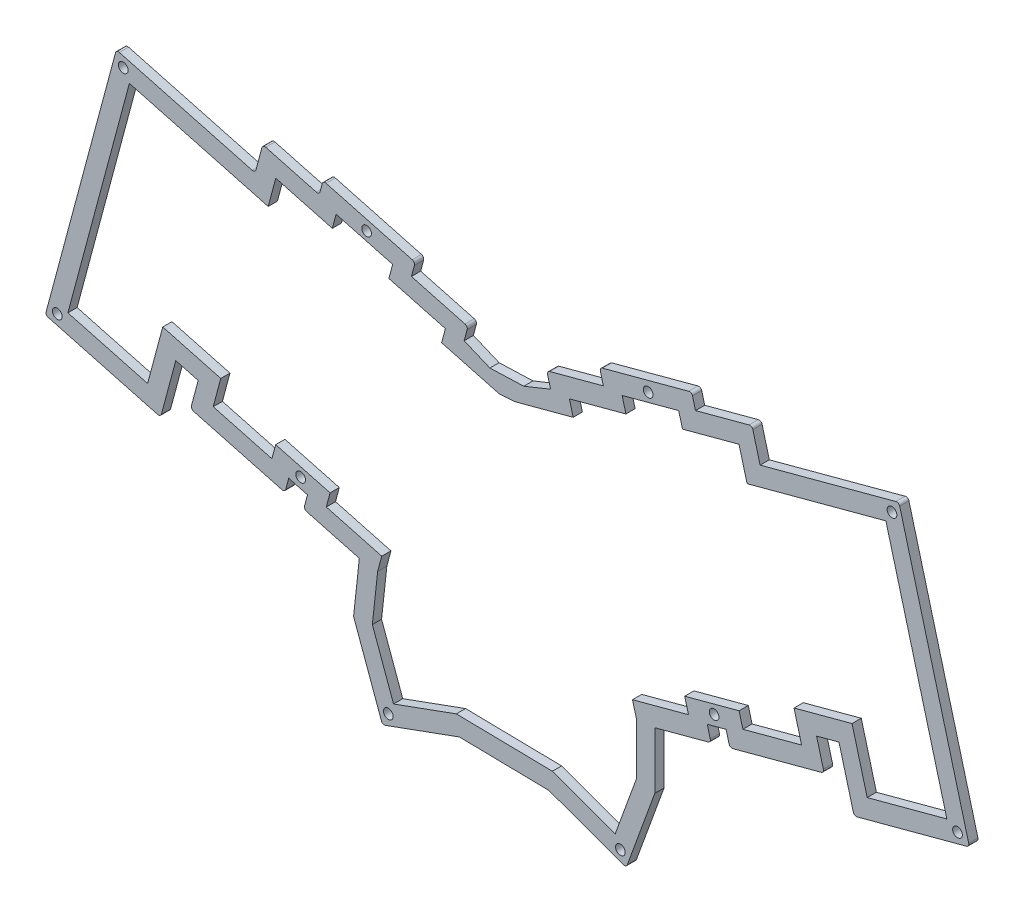
SolidWorks part; units mm, degrees
ref_plane "Front Plane" through (0, 0, 0) normal (0, 0, 1) x (1, 0, 0)
ref_plane "Top Plane" through (0, 0, 0) normal (0, 1, 0) x (1, 0, 0)
ref_plane "Right Plane" through (0, 0, 0) normal (1, 0, 0) x (0, 0, -1)
sketch "Model" plane through (0, 0, 0) normal (0, 0, 1) x (1, 0, 0)
  line L0 (282.165, 226.202) -> (288.4436, 227.8841) construction
  line L1 (267.373, 281.405) -> (273.6516, 283.0871) construction
  line L2 (195.392, 284.0785) -> (194.5766, 287.1211) construction
  line L3 (100.681, 283.685) -> (101.4961, 286.7277) construction
  line L4 (168.22, 168.742) -> (181.234, 164.006) construction
  line L5 (181.234, 164.006) -> (185.972, 177.021) construction
  line L6 (185.972, 177.021) -> (172.956, 181.758) construction
  line L7 (172.956, 181.758) -> (168.22, 168.742) construction
  line L8 (132.176, 184.752) -> (133.281, 181.717) construction
  line L9 (133.281, 181.717) -> (131.706, 181.144) construction
  line L10 (131.706, 181.144) -> (130.099, 185.56) construction
  line L11 (130.099, 185.56) -> (117.085, 180.823) construction
  line L12 (117.085, 180.823) -> (118.692, 176.407) construction
  line L13 (118.692, 176.407) -> (117.118, 175.834) construction
  line L14 (117.118, 175.834) -> (116.013, 178.869) construction
  line L15 (116.013, 178.869) -> (109.812, 176.612) construction
  line L16 (109.812, 176.612) -> (110.917, 173.576) construction
  line L17 (110.917, 173.576) -> (110.141, 173.294) construction
  line L18 (110.141, 173.294) -> (111.048, 170.804) construction
  line L19 (111.048, 170.804) -> (111.822, 171.086) construction
  line L20 (111.822, 171.086) -> (113.968, 165.194) construction
  line L21 (113.968, 165.194) -> (115.588, 165.784) construction
  line L22 (115.588, 165.784) -> (115.999, 164.656) construction
  line L23 (115.999, 164.656) -> (118.959, 165.734) construction
  line L24 (118.959, 165.734) -> (118.549, 166.861) construction
  line L25 (118.549, 166.861) -> (120.169, 167.452) construction
  line L26 (120.169, 167.452) -> (118.641, 171.651) construction
  line L27 (118.641, 171.651) -> (120.215, 172.224) construction
  line L28 (120.215, 172.224) -> (121.821, 167.809) construction
  line L29 (121.821, 167.809) -> (134.837, 172.545) construction
  line L30 (134.837, 172.545) -> (133.23, 176.962) construction
  line L31 (133.23, 176.962) -> (134.804, 177.535) construction
  line L32 (134.804, 177.535) -> (136.332, 173.335) construction
  line L33 (136.332, 173.335) -> (137.953, 173.925) construction
  line L34 (137.953, 173.925) -> (138.363, 172.796) construction
  line L35 (138.363, 172.796) -> (141.323, 173.874) construction
  line L36 (141.323, 173.874) -> (140.913, 175.001) construction
  line L37 (140.913, 175.001) -> (142.533, 175.592) construction
  line L38 (142.533, 175.592) -> (140.389, 181.483) construction
  line L39 (140.389, 181.483) -> (141.165, 181.766) construction
  line L40 (141.165, 181.766) -> (140.258, 184.256) construction
  line L41 (140.258, 184.256) -> (139.484, 183.974) construction
  line L42 (139.484, 183.974) -> (138.378, 187.009) construction
  line L43 (138.378, 187.009) -> (132.176, 184.752) construction
  line L44 (150.319, 175.258) -> (163.333, 170.521) construction
  line L45 (163.333, 170.521) -> (168.071, 183.535) construction
  line L46 (168.071, 183.535) -> (155.055, 188.273) construction
  line L47 (155.055, 188.273) -> (150.319, 175.258) construction
  line L48 (109.952, 197.835) -> (123.33, 194.251) construction
  line L49 (123.33, 194.251) -> (126.916, 207.629) construction
  line L50 (126.916, 207.629) -> (113.537, 211.213) construction
  line L51 (113.537, 211.213) -> (109.952, 197.835) construction
  line L52 (169.157, 208.022) -> (172.741, 194.644) construction
  line L53 (172.741, 194.644) -> (186.119, 198.228) construction
  line L54 (186.119, 198.228) -> (182.535, 211.607) construction
  line L55 (182.535, 211.607) -> (169.157, 208.022) construction
  line L56 (92.7848, 207.366) -> (106.163, 203.781) construction
  line L57 (106.163, 203.781) -> (109.747, 217.159) construction
  line L58 (109.747, 217.159) -> (96.369, 220.744) construction
  line L59 (96.369, 220.744) -> (92.7848, 207.366) construction
  line L60 (186.326, 217.552) -> (189.91, 204.174) construction
  line L61 (189.91, 204.174) -> (203.288, 207.759) construction
  line L62 (203.288, 207.759) -> (199.704, 221.137) construction
  line L63 (199.704, 221.137) -> (186.326, 217.552) construction
  line L64 (114.883, 216.236) -> (128.261, 212.652) construction
  line L65 (128.261, 212.652) -> (131.845, 226.03) construction
  line L66 (131.845, 226.03) -> (118.467, 229.614) construction
  line L67 (118.467, 229.614) -> (114.883, 216.236) construction
  line L68 (164.226, 226.423) -> (167.812, 213.045) construction
  line L69 (167.812, 213.045) -> (181.19, 216.629) construction
  line L70 (181.19, 216.629) -> (177.604, 230.007) construction
  line L71 (177.604, 230.007) -> (164.226, 226.423) construction
  line L72 (75.6158, 216.896) -> (88.9938, 213.312) construction
  line L73 (88.9938, 213.312) -> (92.5781, 226.69) construction
  line L74 (92.5781, 226.69) -> (79.2, 230.274) construction
  line L75 (79.2, 230.274) -> (75.6158, 216.896) construction
  line L76 (55.9827, 217.227) -> (69.3607, 213.643) construction
  line L77 (69.3607, 213.643) -> (72.9449, 227.021) construction
  line L78 (72.9449, 227.021) -> (59.5672, 230.605) construction
  line L79 (59.5672, 230.605) -> (55.9827, 217.227) construction
  line L80 (203.494, 227.083) -> (207.078, 213.705) construction
  line L81 (207.078, 213.705) -> (220.457, 217.29) construction
  line L82 (220.457, 217.29) -> (216.872, 230.668) construction
  line L83 (216.872, 230.668) -> (203.494, 227.083) construction
  line L84 (223.128, 227.414) -> (226.712, 214.036) construction
  line L85 (226.712, 214.036) -> (240.09, 217.62) construction
  line L86 (240.09, 217.62) -> (236.506, 230.998) construction
  line L87 (236.506, 230.998) -> (223.128, 227.414) construction
  line L88 (12.1157, 219.121) -> (25.4937, 215.536) construction
  line L89 (25.4937, 215.536) -> (29.078, 228.914) construction
  line L90 (29.078, 228.914) -> (15.7, 232.499) construction
  line L91 (15.7, 232.499) -> (12.1157, 219.121) construction
  line L92 (266.995, 229.307) -> (270.579, 215.929) construction
  line L93 (270.579, 215.929) -> (283.957, 219.513) construction
  line L94 (283.957, 219.513) -> (280.373, 232.891) construction
  line L95 (280.373, 232.891) -> (266.995, 229.307) construction
  line L96 (97.7138, 225.767) -> (111.092, 222.183) construction
  line L97 (111.092, 222.183) -> (114.677, 235.56) construction
  line L98 (114.677, 235.56) -> (101.299, 239.145) construction
  line L99 (101.299, 239.145) -> (97.7138, 225.767) construction
  line L100 (181.394, 235.953) -> (184.98, 222.575) construction
  line L101 (184.98, 222.575) -> (198.357, 226.159) construction
  line L102 (198.357, 226.159) -> (194.773, 239.538) construction
  line L103 (194.773, 239.538) -> (181.394, 235.953) construction
  line L104 (40.0473, 231.357) -> (53.425, 227.773) construction
  line L105 (53.425, 227.773) -> (57.0096, 241.151) construction
  line L106 (57.0096, 241.151) -> (43.6316, 244.735) construction
  line L107 (43.6316, 244.735) -> (40.0473, 231.357) construction
  line L108 (239.062, 241.545) -> (242.648, 228.166) construction
  line L109 (242.648, 228.166) -> (256.024, 231.75) construction
  line L110 (256.024, 231.75) -> (252.44, 245.128) construction
  line L111 (252.44, 245.128) -> (239.062, 241.545) construction
  line L112 (119.814, 234.637) -> (133.192, 231.053) construction
  line L113 (133.192, 231.053) -> (136.776, 244.431) construction
  line L114 (136.776, 244.431) -> (123.396, 248.015) construction
  line L115 (123.396, 248.015) -> (119.814, 234.637) construction
  line L116 (159.297, 244.824) -> (162.88, 231.445) construction
  line L117 (162.88, 231.445) -> (176.258, 235.03) construction
  line L118 (176.258, 235.03) -> (172.675, 248.408) construction
  line L119 (172.675, 248.408) -> (159.297, 244.824) construction
  line L120 (80.5462, 235.297) -> (93.9243, 231.713) construction
  line L121 (93.9243, 231.713) -> (97.5099, 245.091) construction
  line L122 (97.5099, 245.091) -> (84.1304, 248.675) construction
  line L123 (84.1304, 248.675) -> (80.5462, 235.297) construction
  line L124 (60.912, 235.628) -> (74.2901, 232.044) construction
  line L125 (74.2901, 232.044) -> (77.8757, 245.422) construction
  line L126 (77.8757, 245.422) -> (64.4977, 249.006) construction
  line L127 (64.4977, 249.006) -> (60.912, 235.628) construction
  line L128 (198.563, 245.484) -> (202.147, 232.106) construction
  line L129 (202.147, 232.106) -> (215.525, 235.692) construction
  line L130 (215.525, 235.692) -> (211.941, 249.069) construction
  line L131 (211.941, 249.069) -> (198.563, 245.484) construction
  line L132 (218.196, 245.814) -> (221.782, 232.436) construction
  line L133 (221.782, 232.436) -> (235.16, 236.021) construction
  line L134 (235.16, 236.021) -> (231.574, 249.399) construction
  line L135 (231.574, 249.399) -> (218.196, 245.814) construction
  line L136 (17.045, 237.521) -> (30.423, 233.937) construction
  line L137 (30.423, 233.937) -> (34.0086, 247.315) construction
  line L138 (34.0086, 247.315) -> (20.6306, 250.899) construction
  line L139 (20.6306, 250.899) -> (17.045, 237.521) construction
  line L140 (262.063, 247.708) -> (265.649, 234.33) construction
  line L141 (265.649, 234.33) -> (279.026, 237.914) construction
  line L142 (279.026, 237.914) -> (275.442, 251.292) construction
  line L143 (275.442, 251.292) -> (262.063, 247.708) construction
  line L144 (102.646, 244.168) -> (116.024, 240.584) construction
  line L145 (116.024, 240.584) -> (119.607, 253.962) construction
  line L146 (119.607, 253.962) -> (106.229, 257.546) construction
  line L147 (106.229, 257.546) -> (102.646, 244.168) construction
  line L148 (176.465, 254.354) -> (180.049, 240.976) construction
  line L149 (180.049, 240.976) -> (193.427, 244.56) construction
  line L150 (193.427, 244.56) -> (189.843, 257.938) construction
  line L151 (189.843, 257.938) -> (176.465, 254.354) construction
  line L152 (44.9778, 249.759) -> (58.3558, 246.174) construction
  line L153 (58.3558, 246.174) -> (61.94, 259.553) construction
  line L154 (61.94, 259.553) -> (48.562, 263.136) construction
  line L155 (48.562, 263.136) -> (44.9778, 249.759) construction
  line L156 (234.133, 259.945) -> (237.717, 246.567) construction
  line L157 (237.717, 246.567) -> (251.095, 250.151) construction
  line L158 (251.095, 250.151) -> (247.511, 263.529) construction
  line L159 (247.511, 263.529) -> (234.133, 259.945) construction
  line L160 (124.743, 253.038) -> (138.122, 249.454) construction
  line L161 (138.122, 249.454) -> (141.707, 262.832) construction
  line L162 (141.707, 262.832) -> (128.329, 266.416) construction
  line L163 (128.329, 266.416) -> (124.743, 253.038) construction
  line L164 (154.365, 263.224) -> (157.951, 249.845) construction
  line L165 (157.951, 249.845) -> (171.329, 253.432) construction
  line L166 (171.329, 253.432) -> (167.743, 266.809) construction
  line L167 (167.743, 266.809) -> (154.365, 263.224) construction
  line L168 (85.477, 253.699) -> (98.855, 250.114) construction
  line L169 (98.855, 250.114) -> (102.439, 263.492) construction
  line L170 (102.439, 263.492) -> (89.0612, 267.076) construction
  line L171 (89.0612, 267.076) -> (85.477, 253.699) construction
  line L172 (65.8442, 254.03) -> (79.2219, 250.443) construction
  line L173 (79.2219, 250.443) -> (82.8065, 263.823) construction
  line L174 (82.8065, 263.823) -> (69.427, 267.407) construction
  line L175 (69.427, 267.407) -> (65.8442, 254.03) construction
  line L176 (193.632, 263.885) -> (197.218, 250.507) construction
  line L177 (197.218, 250.507) -> (210.596, 254.092) construction
  line L178 (210.596, 254.092) -> (207.01, 267.47) construction
  line L179 (207.01, 267.47) -> (193.632, 263.885) construction
  line L180 (213.267, 264.215) -> (216.851, 250.837) construction
  line L181 (216.851, 250.837) -> (230.229, 254.422) construction
  line L182 (230.229, 254.422) -> (226.645, 267.8) construction
  line L183 (226.645, 267.8) -> (213.267, 264.215) construction
  line L184 (21.977, 255.922) -> (35.355, 252.338) construction
  line L185 (35.355, 252.338) -> (38.9378, 265.716) construction
  line L186 (38.9378, 265.716) -> (25.5598, 269.3) construction
  line L187 (25.5598, 269.3) -> (21.977, 255.922) construction
  line L188 (257.132, 266.109) -> (260.718, 252.729) construction
  line L189 (260.718, 252.729) -> (274.096, 256.315) construction
  line L190 (274.096, 256.315) -> (270.512, 269.693) construction
  line L191 (270.512, 269.693) -> (257.132, 266.109) construction
  line L192 (107.575, 262.569) -> (120.953, 258.984) construction
  line L193 (120.953, 258.984) -> (124.539, 272.362) construction
  line L194 (124.539, 272.362) -> (111.161, 275.947) construction
  line L195 (111.161, 275.947) -> (107.575, 262.569) construction
  line L196 (171.534, 272.755) -> (175.118, 259.377) construction
  line L197 (175.118, 259.377) -> (188.496, 262.961) construction
  line L198 (188.496, 262.961) -> (184.912, 276.339) construction
  line L199 (184.912, 276.339) -> (171.534, 272.755) construction
  line L200 (49.9071, 268.159) -> (63.2852, 264.575) construction
  line L201 (63.2852, 264.575) -> (66.8708, 277.953) construction
  line L202 (66.8708, 277.953) -> (53.4928, 281.537) construction
  line L203 (53.4928, 281.537) -> (49.9071, 268.159) construction
  line L204 (229.201, 278.346) -> (232.786, 264.968) construction
  line L205 (232.786, 264.968) -> (246.164, 268.554) construction
  line L206 (246.164, 268.554) -> (242.579, 281.932) construction
  line L207 (242.579, 281.932) -> (229.201, 278.346) construction
  line L208 (90.4074, 272.099) -> (103.785, 268.515) construction
  line L209 (103.785, 268.515) -> (107.37, 281.893) construction
  line L210 (107.37, 281.893) -> (93.992, 285.477) construction
  line L211 (93.992, 285.477) -> (90.4074, 272.099) construction
  line L212 (70.7732, 272.43) -> (84.1513, 268.844) construction
  line L213 (84.1513, 268.844) -> (87.7369, 282.222) construction
  line L214 (87.7369, 282.222) -> (74.3589, 285.808) construction
  line L215 (74.3589, 285.808) -> (70.7732, 272.43) construction
  line L216 (188.703, 282.286) -> (192.286, 268.908) construction
  line L217 (192.286, 268.908) -> (205.664, 272.493) construction
  line L218 (205.664, 272.493) -> (202.081, 285.871) construction
  line L219 (202.081, 285.871) -> (188.703, 282.286) construction
  line L220 (208.336, 282.616) -> (211.92, 269.238) construction
  line L221 (211.92, 269.238) -> (225.298, 272.822) construction
  line L222 (225.298, 272.822) -> (221.714, 286.2) construction
  line L223 (221.714, 286.2) -> (208.336, 282.616) construction
  line L224 (26.9062, 274.323) -> (40.284, 270.739) construction
  line L225 (40.284, 270.739) -> (43.8697, 284.117) construction
  line L226 (43.8697, 284.117) -> (30.4919, 287.701) construction
  line L227 (30.4919, 287.701) -> (26.9062, 274.323) construction
  line L228 (252.203, 284.508) -> (255.786, 271.131) construction
  line L229 (255.786, 271.131) -> (269.165, 274.716) construction
  line L230 (269.165, 274.716) -> (265.581, 288.094) construction
  line L231 (265.581, 288.094) -> (252.203, 284.508) construction
  line L232 (37.1808, 285.909) -> (37.996, 288.9517) construction
  line L233 (28.6991, 281.012) -> (22.4207, 282.6948) construction
  line L234 (18.8047, 217.3285) -> (17.9893, 214.2859) construction
  line L235 (13.9078, 225.81) -> (7.6293, 227.4922) construction
  line L236 (277.268, 217.721) -> (278.0831, 214.6783) construction
  line L237 (271.2035, 292.2232) -> (291.0512, 218.1525)
  line L238 (241.3027, 224.5444) -> (243.7675, 215.3441)
  line L239 (81.0479, 284.015) -> (81.8635, 287.0576) construction
  line L240 (181.234, 164.006) -> (184.194, 162.9285) construction
  line L241 (91.0631, 284.5916) -> (72.6639, 289.5236)
  line L242 (117.85, 274.1545) -> (118.6654, 277.1971) construction
  line L243 (135.018, 264.624) -> (135.8331, 267.6667) construction
  line L244 (161.054, 265.0165) -> (160.2386, 268.0591) construction
  line L245 (178.223, 274.547) -> (177.4079, 277.5897) construction
  line L246 (215.025, 284.408) -> (214.2099, 287.4507) construction
  line L247 (258.892, 286.301) -> (258.2357, 288.7493) construction
  line L248 (196.599, 205.9665) -> (197.4144, 202.9239) construction
  line L249 (92.2965, 289.1937) -> (110.6958, 284.2617)
  line L250 (213.7675, 215.4975) -> (214.5828, 212.4548) construction
  line L251 (233.401, 215.828) -> (234.2161, 212.7853) construction
  line L252 (62.6717, 215.435) -> (61.8566, 212.3923) construction
  line L253 (82.3048, 215.104) -> (81.4897, 212.0613) construction
  line L254 (99.4739, 205.5735) -> (98.6586, 202.5309) construction
  line L255 (35.8867, 229.2106) -> (54.7701, 224.1516)
  line L256 (60.1818, 279.745) -> (60.9969, 282.7877) construction
  line L257 (72.6639, 289.5236) -> (70.1982, 280.3232)
  line L258 (105.8147, 195.273) -> (104.0964, 179.4507)
  line L259 (52.3052, 214.9511) -> (54.7701, 224.1516)
  line L260 (260.1862, 229.6041) -> (265.1156, 211.2042)
  line L261 (203.777, 289.5866) -> (185.3762, 284.6556)
  line L262 (30.9571, 210.8115) -> (35.8867, 229.2106)
  line L263 (141.707, 262.832) -> (142.5224, 265.8746) construction
  line L264 (154.365, 263.224) -> (153.5495, 266.2666) construction
  line L265 (181.234, 164.006) -> (180.1565, 161.046) construction
  line L266 (92.2965, 289.1937) -> (91.0631, 284.5916)
  line L267 (169.4396, 270.5248) -> (150.6904, 265.5004)
  line L268 (110.6958, 284.2617) -> (109.4634, 279.6637)
  line L269 (127.8626, 274.7318) -> (126.6303, 270.1341)
  line L270 (127.8626, 274.7318) -> (109.4634, 279.6637)
  line L271 (260.1862, 229.6041) -> (241.3027, 224.5444)
  line L272 (126.6303, 270.1341) -> (145.3813, 265.1084)
  line L273 (185.3762, 284.6556) -> (186.6084, 280.0546)
  line L274 (142.3447, 270.8715) -> (153.3719, 271.2634)
  line L275 (203.777, 289.5866) -> (205.0099, 284.986)
  line L276 (168.2073, 275.1248) -> (169.4396, 270.5248)
  line L277 (205.0099, 284.986) -> (223.4098, 289.9154)
  line L278 (223.4098, 289.9154) -> (226.0333, 280.1226)
  line L279 (186.6084, 280.0546) -> (168.2073, 275.1248)
  line L280 (104.0964, 179.4507) -> (110.9864, 160.5147)
  line L281 (152.687, 181.7655) -> (183.603, 170.5135) construction
  line L282 (110.5015, 171.0598) -> (141.4185, 182.3092) construction
  line L283 (27.2858, 222.225) -> (33.5644, 220.5428) construction
  line L284 (90.3394, 209.6904) -> (72.6399, 214.4322)
  line L285 (71.4079, 209.8335) -> (72.6399, 214.4322)
  line L286 (89.1069, 205.0898) -> (90.3394, 209.6904)
  line L287 (89.1069, 205.0898) -> (107.1497, 200.256)
  line L288 (107.1497, 200.256) -> (105.8147, 195.273)
  line L289 (110.9864, 160.5147) -> (131.4289, 167.9529)
  line L290 (71.4079, 209.8335) -> (52.3052, 214.9511)
  line L291 (5.0216, 217.7602) -> (25.0282, 292.4264)
  line L292 (130.099, 185.56) -> (121.821, 167.809) construction
  line L293 (190.0384, 195.7708) -> (190.0096, 178.9037)
  line L294 (235.89, 280.139) -> (235.2337, 282.5873) construction
  line L295 (162.6744, 167.408) -> (183.1165, 159.9688)
  line L296 (131.4289, 167.9529) -> (162.6744, 167.408)
  line L297 (5.0216, 217.7602) -> (30.9571, 210.8115)
  line L298 (46.7361, 229.565) -> (45.921, 226.5223) construction
  line L299 (265.1156, 211.2042) -> (291.0512, 218.1525)
  line L300 (25.0282, 292.4264) -> (70.1982, 280.3232)
  line L301 (226.0333, 280.1226) -> (271.2035, 292.2232)
  line L302 (216.1359, 206.6593) -> (215.3122, 209.7329) construction
  line L303 (128.329, 170.177) -> (129.4061, 167.2169) construction
  line L304 (249.336, 229.958) -> (250.1513, 226.9153) construction
  line L305 (268.787, 222.618) -> (262.5084, 220.9359) construction
  line L306 (109.952, 197.835) -> (106.7322, 198.6976) construction
  line L307 (-2.3268, 213.5174) -> (20.7855, 299.7748)
  line L308 (186.119, 198.228) -> (189.1617, 199.0431) construction
  line L309 (206.9661, 205.4835) -> (188.7445, 200.6005)
  line L310 (188.7445, 200.6005) -> (190.0384, 195.7708)
  line L311 (20.7855, 299.7748) -> (65.9558, 287.6716)
  line L312 (68.4216, 296.8725) -> (65.9558, 287.6716)
  line L313 (86.821, 291.9405) -> (68.4216, 296.8725)
  line L314 (88.0544, 296.5426) -> (86.821, 291.9405)
  line L315 (88.0544, 296.5426) -> (118.0445, 288.5037)
  line L316 (118.0445, 288.5037) -> (116.8121, 283.9057)
  line L317 (135.2113, 278.9738) -> (116.8121, 283.9057)
  line L318 (135.2113, 278.9738) -> (133.9791, 274.3762)
  line L319 (133.9791, 274.3762) -> (142.3447, 270.8715)
  line L320 (153.3719, 271.2634) -> (162.0915, 274.7674)
  line L321 (20.7855, 299.7748) -> (25.0282, 292.4264) construction
  line L322 (160.859, 279.3678) -> (162.0915, 274.7674)
  line L323 (179.2607, 284.2977) -> (160.859, 279.3678)
  line L324 (178.0286, 288.8984) -> (179.2607, 284.2977)
  line L325 (208.0195, 296.9352) -> (178.0286, 288.8984)
  line L326 (208.0195, 296.9352) -> (209.2525, 292.3342)
  line L327 (209.2525, 292.3342) -> (227.6528, 297.2637)
  line L328 (227.6528, 297.2637) -> (230.2763, 287.4708)
  line L329 (230.2763, 287.4708) -> (275.4462, 299.5713)
  line L330 (298.3998, 213.9096) -> (294.5027, 216.1597) construction
  line L331 (275.4462, 299.5713) -> (298.3998, 213.9096)
  line L332 (260.8726, 203.856) -> (298.3998, 213.9096)
  line L333 (255.9433, 222.2556) -> (260.8726, 203.856)
  line L334 (255.9433, 222.2556) -> (248.6509, 220.3017)
  line L335 (183.1165, 159.9688) -> (190.0096, 178.9037)
  line L336 (248.6509, 220.3017) -> (251.1158, 211.1012)
  line L337 (220.4222, 202.8783) -> (251.1158, 211.1012)
  line L338 (219.1898, 207.4775) -> (220.4222, 202.8783)
  line L339 (213.082, 205.8412) -> (219.1898, 207.4775)
  line L340 (206.9661, 205.4835) -> (205.7333, 210.084)
  line L341 (223.4323, 214.8256) -> (224.6648, 210.2265)
  line L342 (205.7333, 210.084) -> (223.4323, 214.8256)
  line L343 (214.3147, 201.2411) -> (213.082, 205.8412)
  line L344 (214.3147, 201.2411) -> (196.0393, 196.3437)
  line L345 (224.6648, 210.2265) -> (243.7675, 215.3441)
  line L346 (196.0393, 196.3437) -> (196.0078, 177.8406)
  line L347 (150.6904, 265.5004) -> (170.7656, 190.6076) construction
  line L348 (186.7023, 152.2789) -> (196.0078, 177.8406)
  line L349 (161.566, 161.4264) -> (186.7023, 152.2789)
  line L350 (132.4358, 161.9344) -> (161.566, 161.4264)
  line L351 (107.3996, 152.8248) -> (132.4358, 161.9344)
  line L352 (97.9807, 178.7109) -> (107.3996, 152.8248)
  line L353 (99.8582, 195.9979) -> (97.9807, 178.7109)
  line L354 (141.707, 262.832) -> (154.365, 263.224) construction
  line L355 (81.7586, 200.8468) -> (99.8582, 195.9979)
  line L356 (81.7586, 200.8468) -> (82.9911, 205.4475)
  line L357 (82.9911, 205.4475) -> (76.8829, 207.0839)
  line L358 (75.6509, 202.4852) -> (76.8829, 207.0839)
  line L359 (75.6509, 202.4852) -> (44.9569, 210.7082)
  line L360 (44.9569, 210.7082) -> (47.4218, 219.9086)
  line L361 (40.1295, 221.8623) -> (47.4218, 219.9086)
  line L362 (35.1999, 203.4631) -> (40.1295, 221.8623)
  line L363 (-2.3268, 213.5174) -> (35.1999, 203.4631)
  line L364 (20.7855, 299.7748) -> (23.0356, 295.8777) construction
  line L365 (142.5224, 265.8746) -> (153.5495, 266.2666) construction
  line L366 (275.4462, 299.5713) -> (271.2035, 292.2232) construction
  line L367 (291.0512, 218.1525) -> (298.3998, 213.9096) construction
  line L368 (-2.3268, 213.5174) -> (5.0216, 217.7602) construction
  line L369 (107.3996, 152.8248) -> (110.9864, 160.5147) construction
  line L370 (183.1165, 159.9688) -> (186.7023, 152.2789) construction
  line L371 (107.3996, 152.8248) -> (109.3018, 156.903) construction
  line L372 (184.8006, 156.3573) -> (186.7023, 152.2789) construction
  line L373 (106.163, 203.781) -> (189.91, 204.174) construction
  line L374 (101.4961, 286.7277) -> (103.0495, 292.5232) construction
  line L375 (194.5766, 287.1211) -> (193.0241, 292.9168) construction
  line L376 (23.0356, 295.8777) -> (23.8591, 298.9513) construction
  line L377 (193.0241, 292.9168) -> (193.8474, 289.8432) construction
  line L378 (214.5828, 212.4548) -> (216.1359, 206.6593) construction
  line L379 (103.0495, 292.5232) -> (102.2257, 289.4497) construction
  line L380 (275.4462, 299.5713) -> (273.1961, 295.6743) construction
  line L381 (-2.3268, 213.5174) -> (1.5702, 215.7675) construction
  line L382 (81.4897, 212.0613) -> (79.937, 206.2657) construction
  line L383 (81.4897, 212.0613) -> (79.937, 206.2657) construction
  line L384 (214.5828, 212.4548) -> (216.1359, 206.6593) construction
  line L385 (145.3813, 265.1084) -> (125.265, 190.0622) construction
  line L386 (190.0384, 195.7708) -> (170.7656, 190.6076) construction
  line L387 (148.0359, 266.0706) -> (148.0365, 203.9775) construction
  line L388 (105.8147, 195.273) -> (125.265, 190.0622) construction
  line L389 (104.0964, 179.4507) -> (140.9309, 192.8582) construction
  line L390 (190.0096, 178.9037) -> (153.1726, 192.3111) construction
  line L391 (152.687, 181.7655) -> (149.727, 182.8428) construction
  line L392 (131.4289, 167.9529) -> (146.3042, 173.3654) construction
  line L393 (153.1726, 192.3111) -> (147.152, 175.767) construction
  line L394 (146.3042, 173.3654) -> (162.6744, 167.408) construction
  line L395 (141.4185, 182.3092) -> (144.3786, 183.3863) construction
  line L396 (147.152, 175.767) -> (140.9309, 192.8582) construction
  line L397 (110.5015, 171.0598) -> (107.5414, 169.9827) construction
  line L398 (123.592, 183.1915) -> (122.5136, 186.1545) construction
  line L399 (105.8147, 195.273) -> (183.187, 229.264) construction
  line L400 (171.073, 185.7954) -> (164.1828, 166.8591) construction
  line L401 (112.8845, 228.8715) -> (190.0384, 195.7708) construction
  line L402 (105.8147, 195.273) -> (133.2811, 207.3395) construction
  line L403 (162.4685, 207.5989) -> (190.0384, 195.7708) construction
  line L404 (136.776, 244.431) -> (159.297, 244.824) construction
  line L405 (136.776, 244.431) -> (142.5224, 244.5313) construction
  line L406 (159.297, 244.824) -> (153.5495, 244.7237) construction
  line L407 (79.937, 206.2657) -> (80.7604, 209.3393) construction
  line L408 (145.3813, 265.1084) -> (150.6904, 265.5004)
  line L425 (164.1828, 166.8591) -> (183.1165, 159.9688) construction
  line L426 (190.0096, 178.9037) -> (171.073, 185.7954) construction
  line L427 (99.8582, 195.9979) -> (99.8582, 195.9979) construction
  line L428 (99.8582, 195.9979) -> (97.9807, 178.7109) construction
  line L429 (150.6904, 265.5004) -> (145.3813, 265.1084) construction
  line L430 (149.6841, 271.4425) -> (145.9529, 271.1669) construction
  line L431 (133.9791, 274.3762) -> (145.9529, 271.1669) construction
  line L432 (162.0915, 274.7674) -> (149.6841, 271.4425) construction
  line L433 (256.6831, 294.5449) -> (275.4462, 299.5713) construction
  line L434 (230.2763, 287.4708) -> (256.6831, 294.5449) construction
  line L435 (196.0393, 196.3437) -> (196.0393, 196.3437) construction
  line L436 (196.0393, 196.3437) -> (196.0078, 177.8406) construction
  line L437 (226.0333, 280.1226) -> (258.2357, 288.7493) construction
  line L438 (258.2357, 288.7493) -> (271.2035, 292.2232) construction
  circle A0 centre (23.0356, 295.8777) radius 1.575
  circle A1 centre (109.3018, 156.903) radius 1.575
  circle A2 centre (184.8006, 156.3573) radius 1.575
  circle A3 centre (193.8474, 289.8432) radius 1.575
  circle A4 centre (102.2257, 289.4497) radius 1.575
  circle A5 centre (273.1961, 295.6743) radius 1.575
  circle A6 centre (1.5702, 215.7675) radius 1.575
  circle A7 centre (294.5027, 216.1597) radius 1.575
  circle A8 centre (80.7604, 209.3393) radius 1.575
  circle A9 centre (215.3122, 209.7329) radius 1.575
  circle A10 centre (133.2811, 207.3395) radius 1.575 construction
  circle A11 centre (162.4685, 207.5989) radius 1.575 construction
  circle A12 centre (142.5224, 244.5313) radius 1.575 construction
  circle A13 centre (153.5495, 244.7237) radius 1.575 construction
  point P253 (61.8566, 212.3923)
  point P289 (81.8635, 287.0576)
  point P293 (194.5766, 287.1211)
  point P295 (101.4961, 286.7277)
  point P297 (81.4897, 212.0613)
  point P361 (125.96, 176.6845)
  point P362 (125.96, 176.6845)
  point P374 (214.5828, 212.4548)
  point P377 (234.2161, 212.7853)
  point P378 (177.4079, 277.5897)
  point P386 (214.2099, 287.4507)
  dimension "D5" = 6
  dimension "D4" = 3.15
  dimension "D7" = 30.011
  dimension "D8" = 30
  dimension "D1" = 9.5249
  dimension "D2" = 6.5
  dimension "D3" = 5
  dimension "D6" = 4.5
  dimension "D10" = 4.5
extrude "Boss-Extrude1" add sketch "Model" against normal blind 3
fillet "Fillet1" radius 1 24 edges at (35.1999, 203.4631, -1.5) (44.9569, 210.7082, -1.5) (75.6509, 202.4852, -1.5) (81.7586, 200.8468, -1.5) (107.3996, 152.8248, -1.5) (186.7023, 152.2789, -1.5) (214.3147, 201.2411, -1.5) (220.4222, 202.8783, -1.5) (260.8726, 203.856, -1.5) (251.1158, 211.1012, -1.5) (298.3998, 213.9096, -1.5) (275.4462, 299.5713, -1.5) (227.6528, 297.2637, -1.5) (208.0195, 296.9352, -1.5) (178.0286, 288.8984, -1.5) (160.859, 279.3678, -1.5) (88.0544, 296.5426, -1.5) (135.2113, 278.9738, -1.5) (118.0445, 288.5037, -1.5) (86.821, 291.9405, -1.5) (65.9558, 287.6716, -1.5) (68.4216, 296.8725, -1.5) (20.7855, 299.7748, -1.5) (-2.3268, 213.5174, -1.5)
